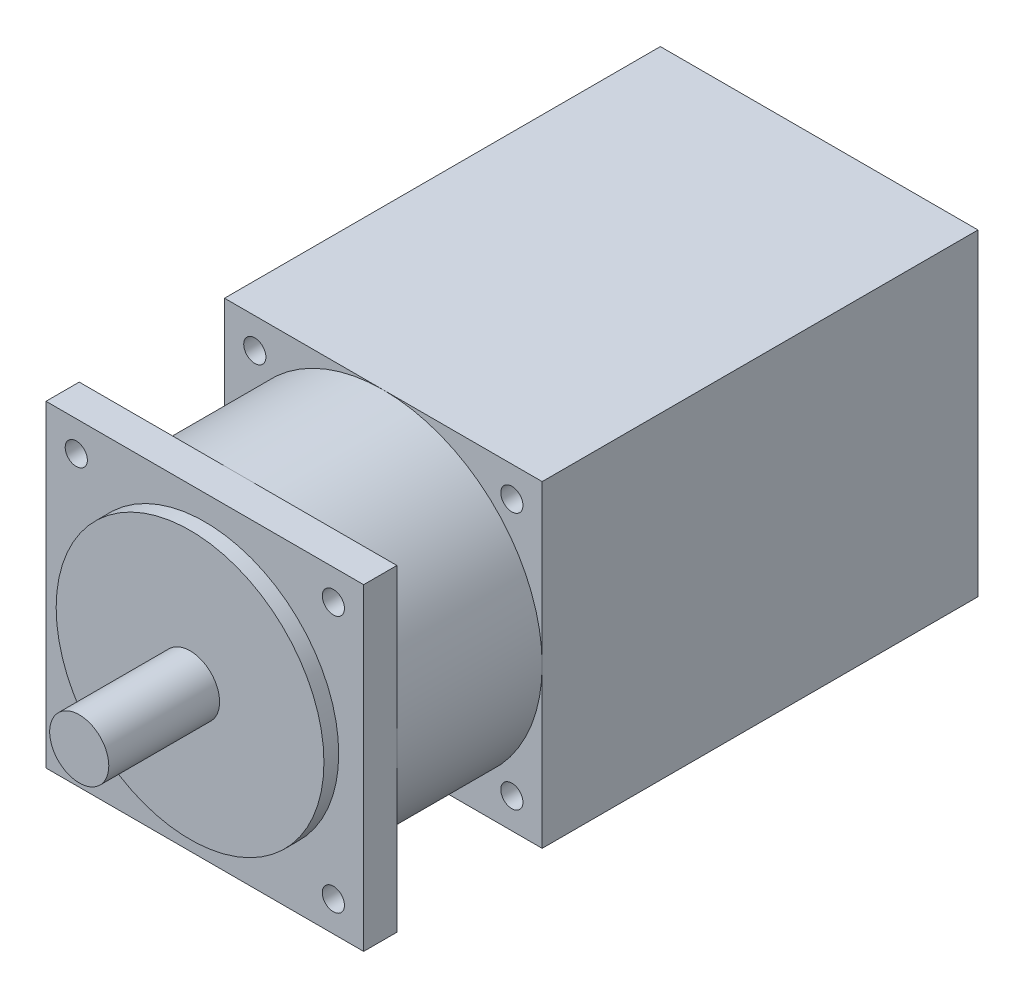
SolidWorks part; units mm, degrees
ref_plane "前视基准面" through (0, 0, 0) normal (0, 0, 1) x (1, 0, 0)
ref_plane "上视基准面" through (0, 0, 0) normal (0, 1, 0) x (1, 0, 0)
ref_plane "右视基准面" through (0, 0, 0) normal (1, 0, 0) x (0, 0, -1)
sketch "草图1" plane through (0, 0, 0) normal (0, 0, 1) x (1, 0, 0)
  line L1 (-43, 43) -> (43, 43)
  line L2 (-43, 43) -> (-43, -43)
  line L3 (-43, -43) -> (43, -43)
  line L4 (43, 43) -> (43, -43)
  line L5 (-43, 43) -> (43, -43) construction
  line L6 (-43, -43) -> (43, 43) construction
  line L7 (-34.8, 34.8) -> (34.8, 34.8) construction
  line L8 (-34.8, 34.8) -> (-34.8, -34.8) construction
  line L9 (-34.8, -34.8) -> (34.8, -34.8) construction
  line L10 (34.8, 34.8) -> (34.8, -34.8) construction
  line L11 (-34.8, 34.8) -> (34.8, -34.8) construction
  line L12 (-34.8, -34.8) -> (34.8, 34.8) construction
  circle A4 centre (-34.8, 34.8) radius 3
  circle A5 centre (34.8, 34.8) radius 3
  circle A6 centre (34.8, -34.8) radius 3
  circle A7 centre (-34.8, -34.8) radius 3
  point P0 (0, 0)
  dimension "D1" = 86
  dimension "D2" = 6
  dimension "D3" = 69.6
  dimension "D4" = 4
extrude "凸台-拉伸1" add sketch "草图1" along normal blind 118
sketch "草图2" plane through (0, 0, 118) normal (0, 0, 1) x (1, 0, 0)
  line L0 (-43, 43) -> (43, -43) construction
  circle A0 centre (0, 0) radius 43
  dimension "D1" = 86
extrude "凸台-拉伸2" add sketch "草图2" along normal blind 39.3333
sketch "草图3" plane through (0, 0, 157.3333) normal (0, 0, 1) x (1, 0, 0)
  line L1 (-43, -43) -> (43, -43)
  line L2 (-43, -43) -> (-43, 43)
  line L3 (-43, 43) -> (43, 43)
  line L4 (43, -43) -> (43, 43)
  line L5 (-43, -43) -> (43, 43) construction
  line L6 (-43, 43) -> (43, -43) construction
  line L7 (-34.8, -34.8) -> (34.8, -34.8) construction
  line L8 (-34.8, -34.8) -> (-34.8, 34.8) construction
  line L9 (-34.8, 34.8) -> (34.8, 34.8) construction
  line L10 (34.8, -34.8) -> (34.8, 34.8) construction
  line L11 (-34.8, -34.8) -> (34.8, 34.8) construction
  line L12 (-34.8, 34.8) -> (34.8, -34.8) construction
  circle A0 centre (-34.8, 34.8) radius 3
  circle A1 centre (34.8, 34.8) radius 3
  circle A2 centre (34.8, -34.8) radius 3
  circle A3 centre (-34.8, -34.8) radius 3
  point P0 (0, 0)
  point P6 (0, 0)
  dimension "D3" = 4
  dimension "D1" = 86
  dimension "D2" = 69.6
extrude "凸台-拉伸3" add sketch "草图3" along normal blind 9
sketch "草图4" plane through (0, 0, 166.3333) normal (0, 0, 1) x (1, 0, 0)
  circle A0 centre (0, 0) radius 36.25
  dimension "D1" = 72.5
extrude "凸台-拉伸4" add sketch "草图4" along normal blind 4
sketch "草图5" plane through (0, 0, 170.3333) normal (0, 0, 1) x (1, 0, 0)
  circle A0 centre (0, 0) radius 8
  dimension "D1" = 16
extrude "凸台-拉伸5" add sketch "草图5" along normal blind 30
